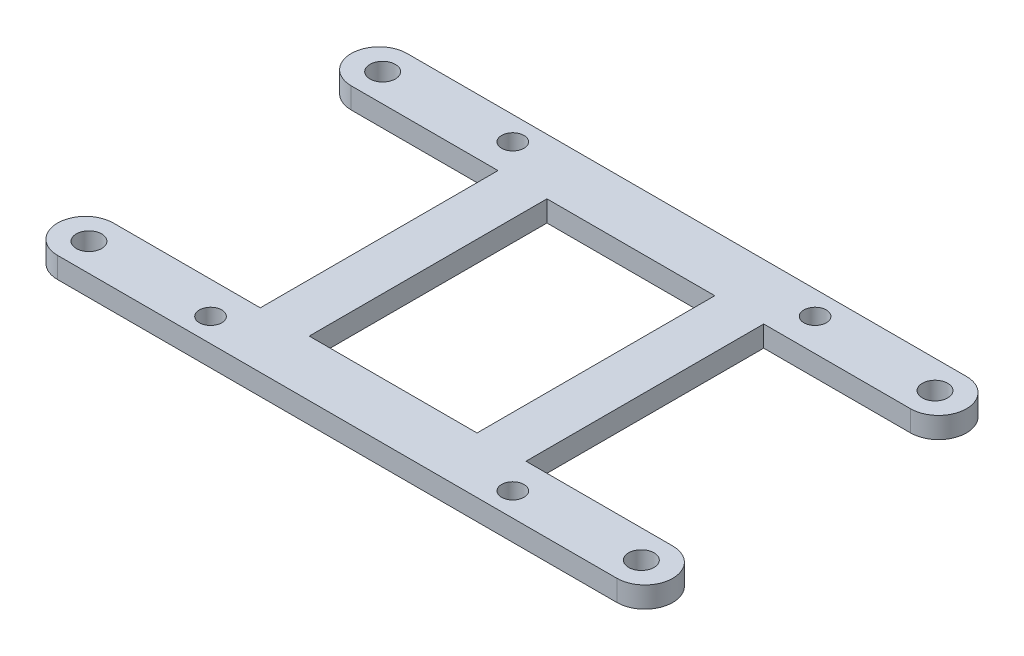
SolidWorks part; units mm, degrees
ref_plane "Front Plane" through (0, 0, 0) normal (0, 0, 1) x (1, 0, 0)
ref_plane "Top Plane" through (0, 0, 0) normal (0, 1, 0) x (1, 0, 0)
ref_plane "Right Plane" through (0, 0, 0) normal (1, 0, 0) x (0, 0, -1)
other "Configuration Table"
sketch "草图1" plane through (0, 0, 0) normal (0, 1, 0) x (1, 0, 0)
  line L0 (19, 17) -> (40, 17)
  line L1 (-12, -17) -> (12, -17)
  line L2 (-12, -17) -> (-12, 17)
  line L3 (-12, 17) -> (12, 17)
  line L4 (12, -17) -> (12, 17)
  line L5 (-12, -17) -> (12, 17) construction
  line L6 (-12, 17) -> (12, -17) construction
  line L7 (19, -25) -> (-19, -25)
  line L8 (19, -17) -> (19, 17)
  line L9 (19, 25) -> (-19, 25)
  line L10 (-19, -17) -> (-19, 17)
  line L11 (19, -25) -> (-19, 25) construction
  line L12 (19, 25) -> (-19, -25) construction
  line L15 (19, 25) -> (40, 25)
  line L16 (44, 17) -> (44, 25)
  line L17 (-40, 17) -> (-19, 17)
  line L18 (-40, 25) -> (-19, 25)
  line L20 (-40, -25) -> (-19, -25)
  line L21 (-40, -17) -> (-19, -17)
  line L23 (19, -25) -> (40, -25)
  line L24 (19, -17) -> (40, -17)
  line L26 (-44, 25) -> (-44, 17) construction
  line L28 (0, 42.7152) -> (0, 36.9107) construction
  line L29 (-19, 17) -> (-19, 25) [skipped]
  line L30 (-19, -25) -> (-19, -17) [skipped]
  line L31 (0, 0) -> (42.1795, 0) construction
  line L32 (44, -25) -> (44, -17) [skipped]
  arc A0 (-40, 25) -> (-40, 17) centre (-40, 21) ccw
  arc A1 (40, 25) -> (40, 17) centre (40, 21) cw
  arc A2 (40, -25) -> (40, -17) centre (40, -21) ccw
  arc A3 (-40, -25) -> (-40, -17) centre (-40, -21) cw
  circle A4 centre (-39.5, -21) radius 1.8172
  circle A5 centre (39.5, -21) radius 1.8172
  circle A6 centre (39.5, 21) radius 1.8172
  circle A7 centre (-39.5, 21) radius 1.8172
  circle A8 centre (-21.5, 21.615) radius 1.6
  circle A12 centre (21.73, 21.615) radius 1.6
  circle A13 centre (21.73, -21.615) radius 1.6
  circle A14 centre (-21.5, -21.615) radius 1.6
  point P0 (0, 0)
  point P6 (0, 0)
  dimension "D9" = 21
  dimension "D14" = 3.6345
  dimension "D20" = 3.2
  dimension "D1" = 34
  dimension "D2" = 24
  dimension "D3" = 38
  dimension "D4" = 50
  dimension "D5" = 25
  dimension "D6" = 2
  dimension "D8" = 4
  dimension "D10" = 40
  dimension "D11" = 4
  dimension "D12" = 4
  dimension "D13" = 38
  dimension "D15" = 39.5
  dimension "D18" = 79
  dimension "D19" = 42
  dimension "D21" = 21.5
  dimension "D22" = 21.615
  dimension "D7" = 2
  dimension "D16" = 2
  dimension "D17" = 2
  dimension "D23" = 2
  dimension "D24" = 2
extrude "凸台-拉伸1" add sketch "草图1" along normal blind 3 contours A3 L20 L7 L23 A2 L24 L8 L0 A1 L15 L9 L18 A0 L17 L10 L21 A7 A6 A5 A4 L4 L1 L2 L3
